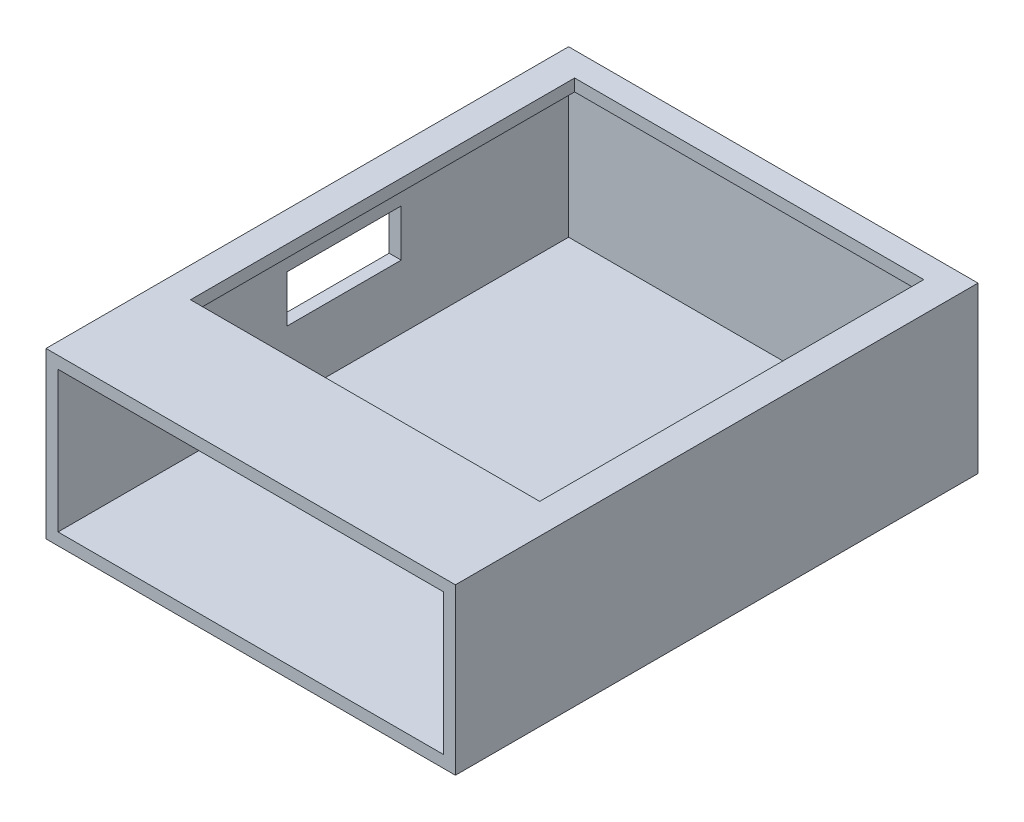
SolidWorks part; units mm, degrees
ref_plane "前视基准面" through (0, 0, 0) normal (0, 0, 1) x (1, 0, 0)
ref_plane "上视基准面" through (0, 0, 0) normal (0, 1, 0) x (1, 0, 0)
ref_plane "右视基准面" through (0, 0, 0) normal (1, 0, 0) x (0, 0, -1)
other "Configuration Table"
sketch "草图1" plane through (0, 0, 0) normal (0, 1, 0) x (1, 0, 0)
  line L0 (0, 0) -> (32, 0)
  line L1 (32, 0) -> (32, 42.4)
  line L2 (32, 42.4) -> (0, 42.4)
  line L3 (0, 42.4) -> (0, 0)
extrude "凸台-拉伸1" add sketch "草图1" along normal blind 11.7
shell "抽壳1" thickness 1
sketch "草图2" plane through (-1, 0, 0) normal (-1, 0, 0) x (0, 0, 1)
  line L0 (-28.5, 9.2) -> (-19, 9.2)
  line L1 (-19, 9.2) -> (-19, 5.3)
  line L2 (-19, 5.3) -> (-28.5, 5.3)
  line L3 (-28.5, 5.3) -> (-28.5, 9.2)
  line L10 (-11.25, 8.3) -> (-9.65, 8.3)
  line L11 (-9.65, 8.3) -> (-9.65, 6.1)
  line L12 (-9.65, 6.1) -> (-12.85, 6.1)
  line L13 (-12.85, 6.1) -> (-12.85, 8.3)
  line L14 (-12.85, 8.3) -> (-11.25, 8.3)
  point P5 (-11.25, 8.3)
  point P19 (-23.75, 9.2)
extrude "切除-左侧接口" cut sketch "草图2" against normal up to next contours L14 L10 L11 L12 L13 | L3 L0 L1 L2
sketch "草图4" plane through (0, 11.7, 0) normal (0, 1, 0) x (1, 0, 0)
  line L0 (-1, 0) -> (33, 0)
  line L1 (33, 0) -> (33, 3)
  line L2 (33, 0) -> (33, 43.4) construction
  line L3 (30.5, 9.5) -> (1.5, 9.5)
  line L4 (-1, 43.4) -> (-1, 0) construction
  line L5 (-1, 3) -> (-1, 0)
  line L6 (-1, 43.4) -> (-1, 0)
  line L7 (33, 0) -> (33, 43.4)
  line L8 (33, 43.4) -> (-1, 43.4)
  line L9 (-1, 43.4) -> (-1, 40.4)
  line L10 (1.5, 41.4) -> (30.5, 41.4)
  line L11 (-1, 43.4) -> (-1, 0)
  line L12 (33, 0) -> (-1, 0)
  line L13 (1.5, 41.4) -> (1.5, 9.5)
  line L14 (30.5, 41.4) -> (30.5, 9.5)
  line L15 (33, 0) -> (33, 43.4)
extrude "凸台-拉伸2" add sketch "草图4" along normal blind 1 contours L8 L6 L0 L7 | L3 L13 L10 L14
